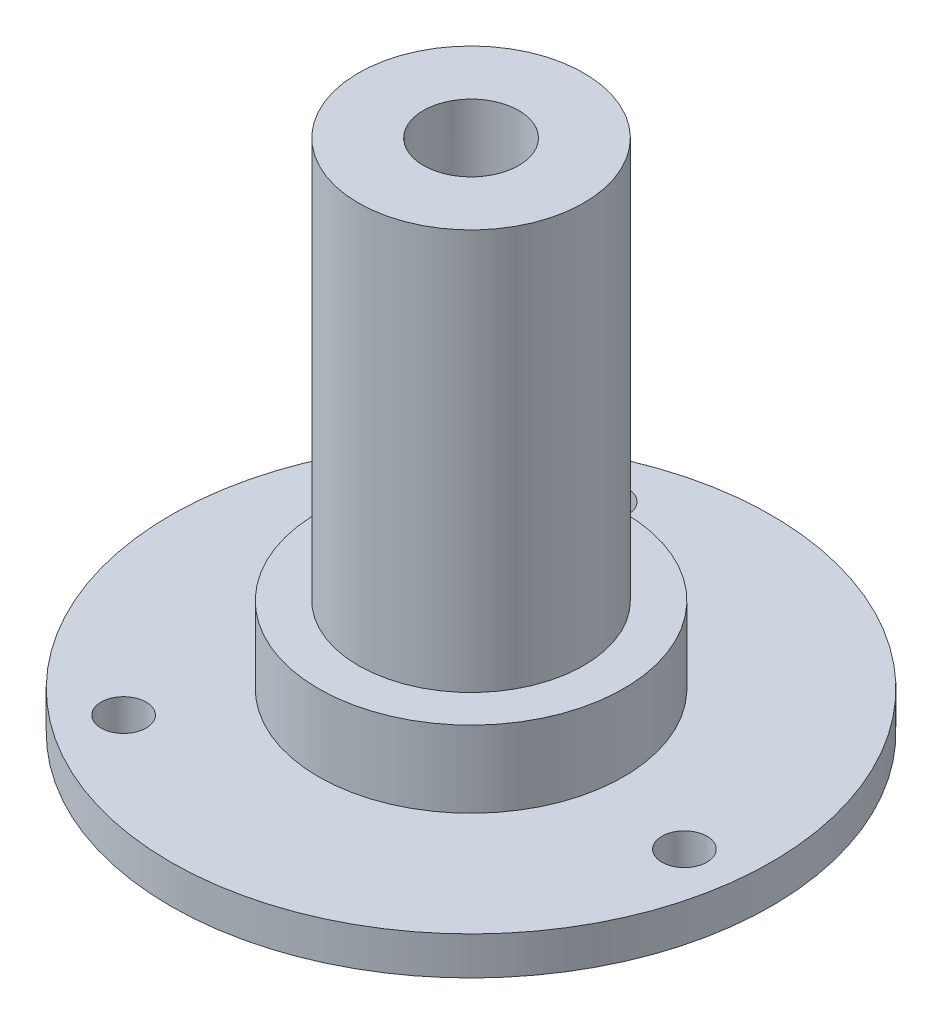
SolidWorks part; units mm, degrees
ref_plane "Front Plane" through (0, 0, 0) normal (0, 0, 1) x (1, 0, 0)
ref_plane "Top Plane" through (0, 0, 0) normal (0, 1, 0) x (1, 0, 0)
ref_plane "Right Plane" through (0, 0, 0) normal (1, 0, 0) x (0, 0, -1)
sketch "Sketch1" plane through (0, 0, 0) normal (0, 1, 0) x (1, 0, 0)
  circle A0 centre (0, 0) radius 20
extrude "Boss-Extrude1" add sketch "Sketch1" along normal blind 2.54
sketch "Sketch2" plane through (0, 2.54, 0) normal (0, 1, 0) x (1, 0, 0)
  circle A0 centre (0, 0) radius 7.5
  dimension "D1" = 15
extrude "Boss-Extrude2" add sketch "Sketch2" along normal blind 31.75
sketch "Sketch6" plane through (0, 0, 0) normal (0, -1, 0) x (-1, 0, 0)
  circle A0 centre (6.3138, 15.2429) radius 1.5
  circle A1 centre (10.0438, -13.0894) radius 1.5
  circle A2 centre (-16.3576, -2.1535) radius 1.5
  dimension "D1" = 3
extrude "Cut-Extrude2" cut sketch "Sketch6" against normal through all
sketch "Sketch7" plane through (0, 34.29, 0) normal (0, 1, 0) x (1, 0, 0)
  circle A0 centre (0, 0) radius 3.175
extrude "Cut-Extrude3" cut sketch "Sketch7" against normal through all
sketch "Sketch8" plane through (0, 0, 0) normal (1, 0, 0) x (0, 0, -1)
  line L1 (7.5, 34.29) -> (-7.5, 34.29) construction
  circle A0 centre (0, 22.29) radius 1.397
  dimension "D1" = 2.794
  dimension "D2" = 12
extrude "Cut-Extrude4" cut sketch "Sketch8" against normal through all
sketch "Sketch9" plane through (0, 0, 0) normal (0, 0, 1) x (1, 0, 0)
  line L0 (7.5, 34.29) -> (-7.5, 34.29) construction
  circle A0 centre (0, 27.29) radius 1.397
  dimension "D1" = 7
extrude "Cut-Extrude5" cut sketch "Sketch9" against normal through all
sketch "Sketch10" plane through (0, 2.54, 0) normal (0, 1, 0) x (1, 0, 0)
  circle A0 centre (0, 0) radius 10.16
extrude "Boss-Extrude3" add sketch "Sketch10" along normal blind 5.08
